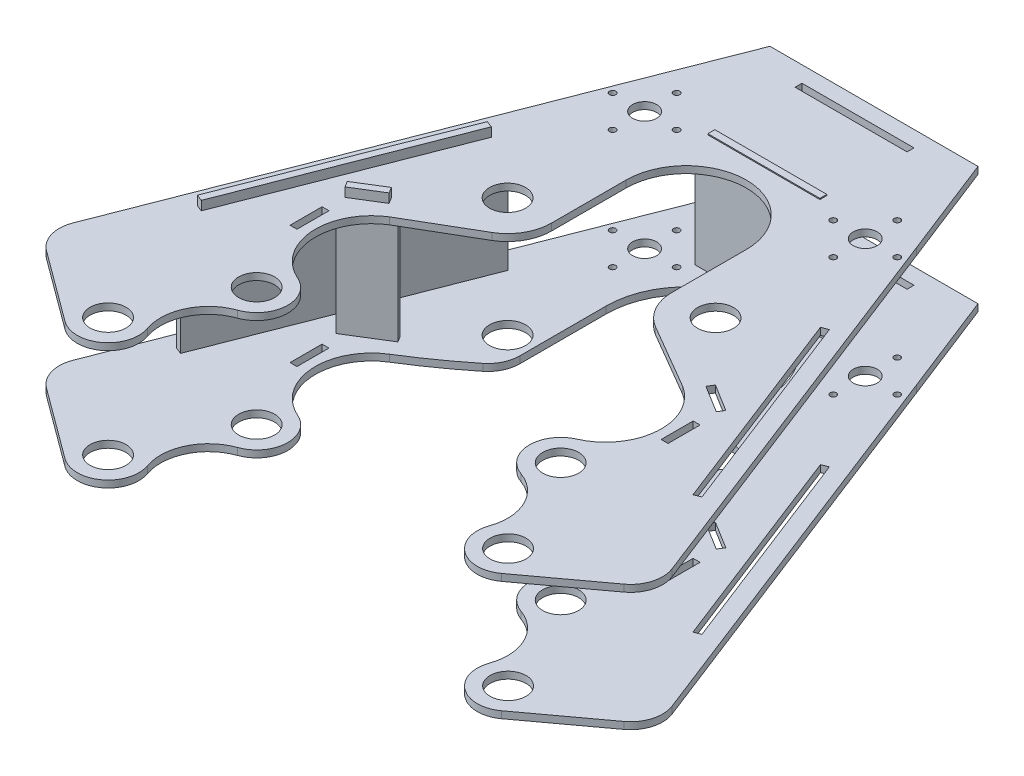
SolidWorks part; units mm, degrees
ref_plane "Alzado" through (0, 0, 0) normal (0, 0, 1) x (1, 0, 0)
ref_plane "Planta" through (0, 0, 0) normal (0, 1, 0) x (1, 0, 0)
ref_plane "Vista lateral" through (0, 0, 0) normal (1, 0, 0) x (0, 0, -1)
sketch "llantas" plane through (0, 0, 0) normal (0, 1, 0) x (1, 0, 0)
  line L0 (0, 221.5734) -> (0, 0) construction
  line L1 (-215.9, 0) -> (0, 0) construction
  circle A0 centre (-93.6625, 101.6) radius 50.8
  circle A1 centre (-215.9, 0) radius 38.1
  circle A2 centre (215.9, 0) radius 38.1
  circle A3 centre (93.6625, 101.6) radius 50.8
  dimension "D1" = 101.6
  dimension "D2" = 42.8625
  dimension "D3" = 177.8
  dimension "D4" = 76.2
  dimension "D5" = 101.6
sketch "cono" plane through (0, 0, 0) normal (1, 0, 0) x (0, 0, -1)
  line L0 (-76.2, 23.114) -> (-22.987, 324.358)
  line L1 (-22.987, 324.358) -> (22.987, 324.358)
  line L2 (0, 324.358) -> (0, 23.114) construction
  line L3 (76.2, 23.114) -> (-76.2, 23.114) construction
  line L4 (-76.2, 23.114) -> (-106.426, 23.114)
  line L5 (-106.426, 23.114) -> (-106.426, 0)
  line L6 (-106.426, 0) -> (106.426, 0)
  line L7 (0, 0) -> (0, 23.114)
  line L8 (-76.2, 23.114) -> (76.2, 23.114)
  line L9 (-80.283, 0) -> (80.283, 0)
  line L10 (221.5734, 0) -> (0, 0) construction
  line L11 (106.426, 23.114) -> (106.426, 0)
  line L12 (76.2, 23.114) -> (106.426, 23.114)
  line L13 (76.2, 23.114) -> (22.987, 324.358)
  line L14 (0, 220.8278) -> (41.275, 220.8278) construction
  dimension "D1" = 324.358
  dimension "D2" = 23.114
  dimension "D3" = 22.987
  dimension "D4" = 152.4
  dimension "D5" = 212.852
  dimension "D6" = 41.275
  dimension "D7" = 220.8278
sketch "TP" plane through (0, 0, 0) normal (0, 1, 0) x (1, 0, 0)
  line L0 (-182.3767, 145.0956) -> (-109.04, 83.339) construction
  line L1 (-225.8697, 11.9948) -> (-103.6322, 113.5948) construction
  line L2 (-205.9303, -11.9948) -> (-83.6928, 89.6052) construction
  line L5 (0, -240.8862) -> (0, 250.9182) construction
  line L8 (205.9303, -11.9948) -> (83.6928, 89.6052) construction
  line L9 (225.8697, 11.9948) -> (103.6322, 113.5948) construction
  line L10 (-84.2938, 123.5581) -> (-172.4782, 161.1832) construction
  line L12 (84.2938, 123.5581) -> (172.4782, 161.1832) construction
  line L13 (182.3767, 145.0956) -> (109.04, 83.339) construction
  arc A0 (-83.6928, 89.6052) -> (-103.6322, 113.5948) centre (-93.6625, 101.6) ccw construction
  arc A2 (-225.8697, 11.9948) -> (-205.9303, -11.9948) centre (-215.9, 0) ccw construction
  arc A7 (225.8697, 11.9948) -> (205.9303, -11.9948) centre (215.9, 0) cw construction
  arc A8 (83.6928, 89.6052) -> (103.6322, 113.5948) centre (93.6625, 101.6) cw construction
  arc A10 (-172.4782, 161.1832) -> (-182.3767, 145.0956) centre (-176.2257, 152.4) ccw construction
  arc A12 (-109.04, 83.339) -> (-84.2938, 123.5581) centre (-93.6625, 101.6) ccw construction
  circle A13 centre (-176.2257, 152.4) radius 30
  arc A14 (109.04, 83.339) -> (84.2938, 123.5581) centre (93.6625, 101.6) cw construction
  arc A15 (172.4782, 161.1832) -> (182.3767, 145.0956) centre (176.2257, 152.4) cw construction
  circle A16 centre (176.2257, 152.4) radius 30
  point P3 (-184.3588, 157.4042)
  point P29 (184.3588, 157.4042)
  dimension "D1" = 31.1944
  dimension "D2" = 47.7465
  dimension "D3" = 19.0986
  dimension "D4" = 60
  dimension "D6" = 50.8
sketch "Croquis4" plane through (0, 0, 0) normal (0, 1, 0) x (1, 0, 0)
  line L11 (0, 293.4478) -> (0, -300.8756) construction
  circle A36 centre (0, 179.087) radius 32.258
  dimension "D4" = 64.516
sketch "Croquis6" plane through (0, 0, 0) normal (0, 1, 0) x (1, 0, 0)
  circle A0 centre (-215.9, 0) radius 14.2875
  circle A1 centre (-93.6625, 101.6) radius 14.2875
  circle A2 centre (93.6625, 101.6) radius 14.2875
  circle A3 centre (215.9, 0) radius 14.2875
  dimension "D1" = 28.575
ref_plane "Plano1" through (0, 184.15, 0) normal (0, 1, 0) x (1, 0, 0)
sketch "Croquis11" plane through (0, 184.15, 0) normal (0, 1, 0) x (1, 0, 0)
  line L0 (0, -106.426) -> (0, 106.426) construction
  line L1 (-97.0214, 55.7432) -> (-110.9758, -55.6685) construction
  line L2 (0, 0) -> (0, -47.7539) construction
  line L3 (-78.2114, 56.5691) -> (-54.5457, -53.1907) construction
  line L4 (-102.0644, -224.6803) -> (-63.9644, -63.6256) construction
  line L5 (-139.2356, -215.8869) -> (-101.1356, -54.8321) construction
  line L6 (0, 0) -> (-82.55, -59.2289) construction
  line L7 (0, 0) -> (0, -106.426) construction
  line L14 (-137.8866, -212.0584) -> (-175.9866, -291.9003) construction
  line L15 (-103.4134, -228.5088) -> (-141.5134, -308.3507) construction
  line L16 (0, 293.4478) -> (0, -300.8756) construction
  circle A0 centre (0, 0) radius 47.7539 construction
  circle A1 centre (-82.55, -59.2289) radius 50.8
  circle A2 centre (-87.5461, 54.5564) radius 30
  arc A3 (-78.2114, 56.5691) -> (-97.0214, 55.7432) centre (-87.5461, 54.5564) ccw construction
  arc A4 (-110.9758, -55.6685) -> (-54.5457, -53.1907) centre (-82.55, -59.2289) ccw construction
  circle A5 centre (-120.65, -220.2836) radius 38.1
  arc A6 (-139.2356, -215.8869) -> (-102.0644, -224.6803) centre (-120.65, -220.2836) ccw construction
  arc A7 (-63.9644, -63.6256) -> (-101.1356, -54.8321) centre (-82.55, -59.2289) ccw construction
  circle A12 centre (-120.65, -220.2836) radius 50.8 construction
  circle A13 centre (-158.75, -300.1255) radius 28.575
  arc A14 (-175.9866, -291.9003) -> (-141.5134, -308.3507) centre (-158.75, -300.1255) ccw construction
  arc A15 (-103.4134, -228.5088) -> (-139.2356, -215.8869) centre (-120.65, -220.2836) ccw construction
  dimension "D4" = 60
  dimension "D1" = 101.6
  dimension "D5" = 19.0986
  dimension "D6" = 57.2958
  dimension "D8" = 76.2
  dimension "D10" = 38.1972
  dimension "D17" = 101.6
  dimension "D13" = 57.15
  dimension "D14" = 38.1972
  dimension "D2" = 101.6
  dimension "D3" = 165.1
  dimension "D9" = 165.1
  dimension "D12" = 25.4
  dimension "D16" = 158.75
sketch "Croquis40" plane through (0, 184.15, 0) normal (0, 1, 0) x (1, 0, 0)
  line L0 (-117.475, -110.0289) -> (117.475, -110.0289) construction
  line L1 (-117.475, -110.0289) -> (-117.475, -344.9789) construction
  line L2 (117.475, -110.0289) -> (117.475, -344.9789) construction
  line L3 (-117.475, -344.9789) -> (117.475, -344.9789) construction
  line L4 (0, 0) -> (0, -110.0289)
  circle A1 centre (-82.55, -59.2289) radius 50.8 construction
  dimension "D1" = 234.95
ref_plane "Plano2" through (0, 95.25, 0) normal (0, 1, 0) x (1, 0, 0)
sketch "Croquis12" plane through (0, 95.25, 0) normal (0, 1, 0) x (1, 0, 0)
  line L0 (0, 0) -> (0, -63.4576) construction
  circle A0 centre (0, 0) radius 63.4576 construction
  circle A1 centre (-82.55, -59.2289) radius 50.8
  circle A2 centre (-82.55, -59.2289) radius 50.8 construction
sketch "Croquis13" plane through (0, 184.15, 0) normal (0, 1, 0) x (1, 0, 0)
  line L3 (-47.7539, -59.2289) -> (-47.7539, 0)
  line L4 (0, -106.426) -> (0, 106.426) construction
  line L5 (-114.0873, 68.5409) -> (-82.55, 149.0708)
  line L7 (0, 0) -> (0, 84.5564) construction
  line L8 (47.7539, -59.2289) -> (47.7539, 0)
  line L12 (-82.55, 149.0708) -> (82.55, 149.0708)
  line L13 (114.0873, 68.5409) -> (82.55, 149.0708)
  line L16 (0, 0) -> (0, -218.6479) construction
  line L19 (-139.2356, -215.8869) -> (-101.1356, -54.8321) construction
  line L20 (-116.3683, -119.2231) -> (-65.0245, -89.2892)
  line L23 (116.3683, -119.2231) -> (65.0245, -89.2892)
  line L24 (173.2539, -319.8058) -> (229.1339, -278.6236)
  line L25 (-237.7334, -248.9591) -> (-114.0873, 68.5409)
  line L26 (-173.2539, -319.8058) -> (-229.1339, -278.6236)
  line L27 (237.7334, -248.9591) -> (114.0873, 68.5409)
  circle A0 centre (-87.5461, 54.5564) radius 30 construction
  circle A4 centre (-120.65, -220.2836) radius 14.2875
  circle A9 centre (0, 0) radius 47.7539 construction
  arc A10 (-47.7539, 0) -> (47.7539, 0) centre (0, 0) cw
  circle A13 centre (-82.55, -59.2289) radius 14.2875
  circle A14 centre (-87.5461, 54.5564) radius 9.525
  circle A15 centre (-87.5461, 79.9564) radius 2.4892
  circle A16 centre (-87.5461, 54.5564) radius 25.4 construction
  circle A17 centre (-112.9461, 54.5564) radius 2.4892
  circle A18 centre (-62.1461, 54.5564) radius 2.4892
  circle A19 centre (-87.5461, 29.1564) radius 2.4892
  circle A20 centre (87.5461, 54.5564) radius 25.4 construction
  circle A21 centre (87.5461, 29.1564) radius 2.4892
  circle A22 centre (62.1461, 54.5564) radius 2.4892
  circle A23 centre (112.9461, 54.5564) radius 2.4892
  circle A24 centre (87.5461, 79.9564) radius 2.4892
  circle A25 centre (87.5461, 54.5564) radius 9.525
  circle A26 centre (82.55, -59.2289) radius 14.2875
  arc A34 (-110.7266, -197.6609) -> (-116.3683, -119.2231) centre (-92.8711, -156.9548) cw
  arc A37 (65.0245, -89.2892) -> (47.7539, -59.2289) centre (82.55, -59.2289) cw
  arc A38 (-47.7539, -59.2289) -> (-65.0245, -89.2892) centre (-82.55, -59.2289) cw
  arc A39 (-173.2539, -319.8058) -> (-135.6711, -292.0603) centre (-158.75, -300.1255) ccw
  arc A40 (-112.411, -243.5727) -> (-135.6711, -292.0603) centre (-99.7041, -279.4913) ccw
  circle A41 centre (-158.75, -300.1255) radius 14.2875
  arc A42 (-112.411, -243.5727) -> (-110.7266, -197.6609) centre (-120.65, -220.2836) ccw
  circle A44 centre (120.65, -220.2836) radius 14.2875
  arc A45 (112.411, -243.5727) -> (135.6711, -292.0603) centre (99.7041, -279.4913) cw
  circle A47 centre (158.75, -300.1255) radius 14.2875
  arc A48 (173.2539, -319.8058) -> (135.6711, -292.0603) centre (158.75, -300.1255) cw
  arc A49 (47.7539, -59.2289) -> (65.0245, -89.2892) centre (82.55, -59.2289) ccw
  arc A50 (229.1339, -278.6236) -> (237.7334, -248.9591) centre (214.0649, -258.1765) ccw
  arc A51 (-229.1339, -278.6236) -> (-237.7334, -248.9591) centre (-214.0649, -258.1765) cw
  arc A54 (112.411, -243.5727) -> (110.7266, -197.6609) centre (120.65, -220.2836) cw
  arc A55 (110.7266, -197.6609) -> (116.3683, -119.2231) centre (92.8711, -156.9548) ccw
  point P66 (0, 149.0708)
  dimension "D2" = 28.575
  dimension "D3" = 28.575
  dimension "D4" = 19.05
  dimension "D5" = 50.8
  dimension "D6" = 4.9784
  dimension "D8" = 10.16
  dimension "D9" = 42.773
  dimension "D10" = 44.45
  dimension "D11" = 38.1
  dimension "D13" = 59.4325
  dimension "D15" = 25.4
  dimension "D18" = 139.7
  dimension "D7" = 165.1
  dimension "D12" = 55.88
  dimension "D14" = 101.6
  dimension "D17" = 317.5
extrude "Saliente-Extruir3" add sketch "Croquis13" along normal blind 5.5
sketch "Croquis15" plane through (0, 95.25, 0) normal (0, 1, 0) x (1, 0, 0)
  line L2 (0, 0) -> (0, 47.7539) construction
  line L3 (0, -80.283) -> (0, 80.283) construction
  line L7 (-237.7334, -248.9591) -> (-114.0873, 68.5409) construction
  line L8 (-114.0873, 68.5409) -> (-82.55, 149.0708) construction
  line L9 (-63.4576, 0) -> (-63.4576, -80.5873)
  line L10 (-237.7334, -248.9591) -> (-114.0873, 68.5409)
  line L11 (-114.0873, 68.5409) -> (-82.55, 149.0708)
  line L15 (-82.55, 149.0708) -> (82.55, 149.0708) construction
  line L16 (-82.55, 149.0708) -> (82.55, 149.0708)
  line L17 (114.0873, 68.5409) -> (82.55, 149.0708)
  line L27 (237.7334, -248.9591) -> (114.0873, 68.5409)
  line L28 (63.4576, 0) -> (63.4576, -80.5873)
  line L29 (-173.2539, -319.8058) -> (-229.1339, -278.6236) construction
  line L30 (-173.2539, -319.8058) -> (-229.1339, -278.6236)
  line L31 (173.2539, -319.8058) -> (229.1339, -278.6236) construction
  line L32 (173.2539, -319.8058) -> (229.1339, -278.6236)
  arc A0 (-116.3683, -119.2231) -> (-110.7266, -197.6609) centre (-92.8711, -156.9548) ccw construction
  circle A1 centre (-120.65, -220.2836) radius 14.2875 construction
  arc A6 (-112.411, -243.5727) -> (-110.7266, -197.6609) centre (-120.65, -220.2836) ccw construction
  arc A7 (-112.411, -243.5727) -> (-135.6711, -292.0603) centre (-99.7041, -279.4913) ccw construction
  circle A8 centre (-158.75, -300.1255) radius 14.2875 construction
  arc A9 (-173.2539, -319.8058) -> (-135.6711, -292.0603) centre (-158.75, -300.1255) ccw construction
  arc A12 (-237.7334, -248.9591) -> (-229.1339, -278.6236) centre (-214.0649, -258.1765) ccw construction
  arc A15 (-116.3683, -119.2231) -> (-110.7266, -197.6609) centre (-92.8711, -156.9548) ccw
  circle A16 centre (-120.65, -220.2836) radius 14.2875
  arc A27 (-112.411, -243.5727) -> (-110.7266, -197.6609) centre (-120.65, -220.2836) ccw
  arc A28 (-112.411, -243.5727) -> (-135.6711, -292.0603) centre (-99.7041, -279.4913) ccw
  circle A29 centre (-158.75, -300.1255) radius 14.2875
  arc A33 (-110.9758, -55.6685) -> (-54.5457, -53.1907) centre (-82.55, -59.2289) ccw construction
  arc A50 (-63.4576, 0) -> (63.4576, 0) centre (0, 0) cw
  circle A51 centre (0, 0) radius 63.4576 construction
  circle A53 centre (0, 0) radius 47.7539 construction
  arc A55 (-116.3683, -119.2231) -> (-63.4576, -80.5873) centre (-351.4154, 258.2154) ccw
  circle A57 centre (-82.55, -59.2289) radius 14.2875 construction
  circle A58 centre (-82.55, -59.2289) radius 14.2875
  circle A59 centre (-112.9461, 54.5564) radius 2.4892 construction
  circle A60 centre (-62.1461, 54.5564) radius 2.4892 construction
  circle A61 centre (-87.5461, 29.1564) radius 2.4892 construction
  circle A62 centre (-87.5461, 54.5564) radius 9.525 construction
  circle A63 centre (-87.5461, 79.9564) radius 2.4892 construction
  circle A64 centre (-112.9461, 54.5564) radius 2.4892
  circle A65 centre (-62.1461, 54.5564) radius 2.4892
  circle A66 centre (-87.5461, 29.1564) radius 2.4892
  circle A67 centre (-87.5461, 54.5564) radius 9.525
  circle A68 centre (-87.5461, 79.9564) radius 2.4892
  circle A69 centre (87.5461, 79.9564) radius 2.4892
  circle A70 centre (87.5461, 54.5564) radius 9.525
  circle A71 centre (87.5461, 29.1564) radius 2.4892
  circle A72 centre (62.1461, 54.5564) radius 2.4892
  circle A73 centre (112.9461, 54.5564) radius 2.4892
  circle A74 centre (82.55, -59.2289) radius 14.2875
  arc A75 (116.3683, -119.2231) -> (63.4576, -80.5873) centre (351.4154, 258.2154) cw
  arc A76 (237.7334, -248.9591) -> (229.1339, -278.6236) centre (214.0649, -258.1765) cw
  arc A78 (173.2539, -319.8058) -> (135.6711, -292.0603) centre (158.75, -300.1255) cw
  circle A79 centre (158.75, -300.1255) radius 14.2875
  arc A80 (112.411, -243.5727) -> (135.6711, -292.0603) centre (99.7041, -279.4913) cw
  arc A81 (112.411, -243.5727) -> (110.7266, -197.6609) centre (120.65, -220.2836) cw
  circle A82 centre (120.65, -220.2836) radius 14.2875
  arc A83 (116.3683, -119.2231) -> (110.7266, -197.6609) centre (92.8711, -156.9548) cw
  arc A84 (-173.2539, -319.8058) -> (-135.6711, -292.0603) centre (-158.75, -300.1255) ccw construction
  arc A85 (-237.7334, -248.9591) -> (-229.1339, -278.6236) centre (-214.0649, -258.1765) ccw construction
  arc A86 (-173.2539, -319.8058) -> (-135.6711, -292.0603) centre (-158.75, -300.1255) ccw
  arc A87 (-237.7334, -248.9591) -> (-229.1339, -278.6236) centre (-214.0649, -258.1765) ccw
  point P62 (173.1328, -319.8945)
  point P85 (0, 0)
extrude "Saliente-Extruir4" add sketch "Croquis15" against normal blind 5.5 separate body
fillet "Redondeo3" radius 25.4 2 edges at (63.4576, 92.5, 80.5873) (-63.4576, 92.5, 80.5873)
sketch "Croquis16" plane through (0, 184.15, 0) normal (0, 1, 0) x (1, 0, 0)
  line L0 (130.6226, -24.0715) -> (135.7476, -22.0756)
  line L1 (130.6226, -24.0715) -> (195.1443, -189.7512)
  line L3 (195.1443, -189.7512) -> (200.2694, -187.7553)
  line L5 (0, 0) -> (0, -255.8326) construction
  line L6 (-195.1443, -189.7512) -> (-200.2694, -187.7553)
  line L7 (-130.6226, -24.0715) -> (-135.7476, -22.0756)
  line L8 (-135.7476, -22.0756) -> (-200.2694, -187.7553)
  line L9 (-130.6226, -24.0715) -> (-195.1443, -189.7512)
  line L10 (135.7476, -22.0756) -> (200.2694, -187.7553)
  line L11 (237.7334, -248.9591) -> (114.0873, 68.5409) construction
  circle A0 centre (87.5461, 54.5564) radius 9.525 construction
  dimension "D3" = 88.9
  dimension "D1" = 12.7
  dimension "D2" = 177.8
  dimension "D4" = 5.5
extrude "Cortar-Extruir5" cut sketch "Croquis16" against normal through all and the other way through all
sketch "Croquis17" plane through (0, 95.25, 0) normal (0, 1, 0) x (1, 0, 0)
  line L0 (-135.7476, -22.0756) -> (-130.6226, -24.0715)
  line L1 (-135.7476, -22.0756) -> (-200.2694, -187.7553)
  line L2 (-130.6226, -24.0715) -> (-195.1443, -189.7512)
  line L3 (-200.2694, -187.7553) -> (-195.1443, -189.7512)
  line L5 (-195.1443, -189.7512) -> (-130.6226, -24.0715) construction
  line L6 (-135.7476, -22.0756) -> (-200.2694, -187.7553) construction
  line L7 (-200.2694, -187.7553) -> (-195.1443, -189.7512) construction
  point P0 (-200.2694, -187.7553)
  point P8 (0, 0)
  point P9 (0, 0)
  point P10 (-135.7476, -22.0756)
  point P12 (-130.6226, -24.0715)
  point P14 (-194.323, -187.6423)
extrude "Saliente-Extruir5" add sketch "Croquis17" along normal blind 101.6 and the other way blind 12.7 separate body
sketch "Croquis18" plane through (-89.8631, 0, 230.7516) normal (-0.3629, 0, 0.9318) x (0.9318, 0, 0.3629)
  line L0 (-118.483, 184.15) -> (-112.983, 184.15)
  line L1 (-118.483, 184.15) -> (-118.483, 95.25)
  line L2 (-112.983, 184.15) -> (-112.983, 95.25)
  line L3 (-118.483, 95.25) -> (-112.983, 95.25)
  point P0 (-112.983, 95.25)
extrude "Saliente-Extruir7" add sketch "Croquis18" along normal blind 12.7
sketch "Croquis19" plane through (-25.3413, 0, 65.0718) normal (0.3629, 0, -0.9318) x (-0.9318, 0, -0.3629)
  line L0 (112.983, 184.15) -> (118.483, 184.15)
  line L1 (112.983, 184.15) -> (112.983, 95.25)
  line L2 (118.483, 184.15) -> (118.483, 95.25)
  line L3 (112.983, 95.25) -> (118.483, 95.25)
  line L5 (263.4114, 95.25) -> (-263.4114, 95.25) construction
  line L6 (263.4114, 184.15) -> (-263.4114, 184.15) construction
  line L7 (118.483, 82.55) -> (118.483, 196.85) construction
  line L8 (112.983, 82.55) -> (112.983, 196.85) construction
  point P0 (120.2195, 184.15)
extrude "Saliente-Extruir8" add sketch "Croquis19" along normal blind 10.16
sketch "Croquis26" plane through (0, 184.15, 0) normal (0, 1, 0) x (1, 0, 0)
  line L0 (-46.2711, 69) -> (-46.2711, 63.5)
  line L1 (-46.2711, 69) -> (42.6289, 69)
  line L2 (-46.2711, 63.5) -> (42.6289, 63.5)
  line L3 (42.6289, 69) -> (42.6289, 63.5)
  line L4 (0, 149.0708) -> (0, 136.3708) construction
  line L5 (-44.45, 136.3708) -> (-44.45, 130.8708)
  line L6 (-44.45, 136.3708) -> (44.45, 136.3708)
  line L7 (-44.45, 130.8708) -> (44.45, 130.8708)
  line L8 (44.45, 136.3708) -> (44.45, 130.8708)
  line L9 (0, 293.4478) -> (0, -300.8756) construction
  line L10 (-82.55, 149.0708) -> (82.55, 149.0708) construction
  circle A0 centre (0, 0) radius 47.7539 construction
  circle A1 centre (-87.5461, 54.5564) radius 30 construction
  point P16 (0, 0)
  point P17 (0, 0)
  point P18 (0, 0)
  point P19 (0, 136.3708)
  point P22 (0, 149.1135)
  point P23 (0, 0)
  dimension "D1" = 88.9
  dimension "D2" = 5.5
  dimension "D3" = 63.5
  dimension "D4" = 41.275
  dimension "D5" = 12.7
extrude "Cortar-Extruir7" cut sketch "Croquis26" against normal through all and the other way through all
sketch "Croquis27" plane through (0, 184.15, 0) normal (0, 1, 0) x (1, 0, 0)
  line L0 (-46.2711, 69) -> (-46.2711, 63.5)
  line L1 (-46.2711, 69) -> (42.6289, 69)
  line L2 (-46.2711, 63.5) -> (42.6289, 63.5)
  line L3 (42.6289, 69) -> (42.6289, 63.5)
  line L5 (-46.2711, 69) -> (-46.2711, 63.5) construction
  line L6 (42.6289, 69) -> (-46.2711, 69) construction
  point P8 (0, 0)
  point P9 (-46.2711, 69)
  point P12 (42.6289, 63.5)
extrude "Saliente-Extruir12" add sketch "Croquis27" along normal blind 6.35 and the other way through all
sketch "Croquis28" plane through (-46.2711, 0, 0) normal (-1, 0, 0) x (0, 0, 1)
  line L0 (-69, 184.15) -> (-63.5, 184.15)
  line L1 (-69, 184.15) -> (-69, 95.25)
  line L2 (-63.5, 184.15) -> (-63.5, 95.25)
  line L3 (-69, 95.25) -> (-63.5, 95.25)
  line L5 (-24.5564, 184.15) -> (-84.5564, 184.15) construction
  line L6 (-63.5, 82.55) -> (-63.5, 190.5) construction
  line L8 (-69, 82.55) -> (-69, 190.5) construction
  line L9 (-69, 95.25) -> (-63.5, 95.25) construction
  point P0 (-69, 95.8726)
extrude "Saliente-Extruir13" add sketch "Croquis28" along normal blind 10.16
sketch "Croquis29" plane through (42.6289, 0, 0) normal (1, 0, 0) x (0, 0, -1)
  line L0 (63.5, 184.15) -> (69, 184.15)
  line L1 (63.5, 184.15) -> (63.5, 95.25)
  line L2 (69, 184.15) -> (69, 95.25)
  line L3 (63.5, 95.25) -> (69, 95.25)
  line L4 (63.5, 82.55) -> (63.5, 190.5) construction
  line L5 (69, 82.55) -> (69, 190.5) construction
  line L9 (63.5, 184.15) -> (69, 184.15) construction
  line L10 (63.5, 95.25) -> (69, 95.25) construction
  point P0 (69, 184.1747)
extrude "Saliente-Extruir14" add sketch "Croquis29" along normal blind 10.16
sketch "Croquis41" plane through (0, 184.15, 0) normal (0, 1, 0) x (1, 0, 0)
  line L0 (128.6379, -105.4141) -> (125.7419, -110.0899)
  line L1 (128.6379, -105.4141) -> (150.2317, -118.7882)
  line L2 (125.7419, -110.0899) -> (147.3357, -123.464)
  line L3 (150.2317, -118.7882) -> (147.3357, -123.464)
  line L5 (0, 0) -> (0, -138.5506) construction
  line L6 (-150.2317, -118.7882) -> (-147.3357, -123.464)
  line L7 (-128.6379, -105.4141) -> (-125.7419, -110.0899)
  line L8 (-125.7419, -110.0899) -> (-147.3357, -123.464)
  line L9 (-128.6379, -105.4141) -> (-150.2317, -118.7882)
  line L15 (144.5211, -139.0036) -> (150.0211, -139.0036)
  line L20 (144.5211, -139.0036) -> (144.5211, -164.4036)
  line L21 (150.0211, -139.0036) -> (150.0211, -164.4036)
  line L22 (144.5211, -164.4036) -> (150.0211, -164.4036)
  line L24 (-144.5211, -164.4036) -> (-150.0211, -164.4036)
  line L25 (-150.0211, -139.0036) -> (-150.0211, -164.4036)
  line L26 (-144.5211, -139.0036) -> (-144.5211, -164.4036)
  line L27 (-144.5211, -139.0036) -> (-150.0211, -139.0036)
  circle A3 centre (82.55, -59.2289) radius 14.2875 construction
  arc A4 (110.7266, -197.6609) -> (116.3683, -119.2231) centre (92.8711, -156.9548) ccw construction
  circle A5 centre (120.65, -220.2836) radius 14.2875 construction
  point P18 (150.0211, -118.6915)
  point P21 (147.2711, -164.4036)
  point P28 (150.0211, -118.5768)
  point P29 (150.0211, -118.7882)
  dimension "D1" = 5.5
  dimension "D2" = 25.4
  dimension "D3" = 63.5
  dimension "D4" = 57.15
  dimension "D5" = 57.15
  dimension "D6" = 55.88
extrude "Cortar-Extruir8" cut sketch "Croquis41" against normal through all and the other way through all
sketch "Croquis42" plane through (0, 184.15, 0) normal (0, 1, 0) x (1, 0, 0)
  line L0 (-128.6379, -105.4141) -> (-125.7419, -110.0899)
  line L1 (-128.6379, -105.4141) -> (-150.2317, -118.7882)
  line L2 (-125.7419, -110.0899) -> (-147.3357, -123.464)
  line L3 (-150.2317, -118.7882) -> (-147.3357, -123.464)
  point P0 (-150.2317, -118.7882)
  point P8 (0, 0)
  point P9 (0, 0)
extrude "Saliente-Extruir15" add sketch "Croquis42" along normal through all and the other way through all separate body
sketch "Croquis43" plane through (-140.1612, 0, 86.8086) normal (0.8502, 0, -0.5265) x (-0.5265, 0, -0.8502)
  line L0 (-27.3849, 184.15) -> (-21.8849, 184.15)
  line L1 (-27.3849, 184.15) -> (-27.3849, 95.25)
  line L2 (-21.8849, 184.15) -> (-21.8849, 95.25)
  line L3 (-27.3849, 95.25) -> (-21.8849, 95.25)
  point P0 (-27.3849, 95.25)
extrude "Saliente-Extruir16" add sketch "Croquis43" along normal blind 5.08
sketch "Croquis44" plane through (-161.755, 0, 100.1827) normal (-0.8502, 0, 0.5265) x (0.5265, 0, 0.8502)
  line L0 (21.8849, 184.15) -> (27.3849, 184.15)
  line L1 (21.8849, 184.15) -> (21.8849, 95.25)
  line L2 (27.3849, 184.15) -> (27.3849, 95.25)
  line L3 (21.8849, 95.25) -> (27.3849, 95.25)
  line L5 (0, 95.25) -> (53.9485, 95.25) construction
  line L6 (21.8849, 196.85) -> (21.8849, 82.55) construction
  point P0 (27.3849, 184.15)
extrude "Saliente-Extruir17" add sketch "Croquis44" along normal blind 5.08
equation "\"D2@TP\"=30*5mm/pi"
equation "\"D3@TP\"=12*5mm/pi"
equation "\"D5@TP\"=(60*5mm)+1mm"
equation "\"D5@Croquis11\"=12*5MM/PI"
equation "\"D6@Croquis11\"=36*5mm/pi"
equation "\"D7@Croquis11\"=(70*5mm)+1mm"
equation "\"D10@Croquis11\"=24*5mm/pi"
equation "\"D11@Croquis11\"=(90*5mm)+1mm"
equation "\"D14@Croquis11\"=24*5mm/pi"
equation "\"D15@Croquis11\"=(60*5mm)+1mm"
